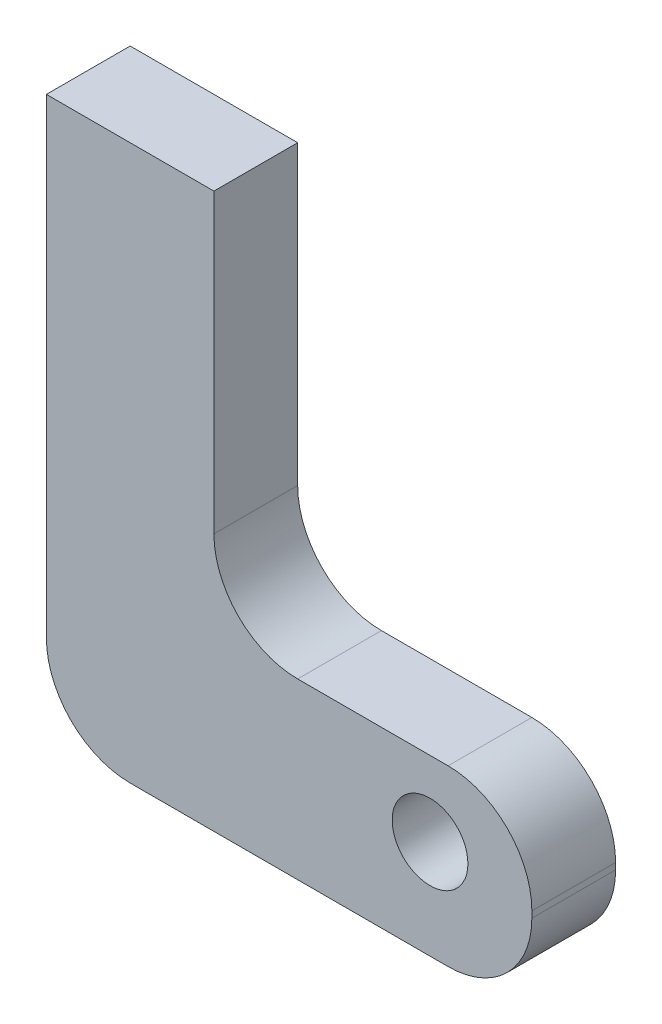
SolidWorks part; units mm, degrees
ref_plane "Front Plane" through (0, 0, 0) normal (0, 0, 1) x (1, 0, 0)
ref_plane "Top Plane" through (0, 0, 0) normal (0, 1, 0) x (1, 0, 0)
ref_plane "Right Plane" through (0, 0, 0) normal (1, 0, 0) x (0, 0, -1)
sketch "Sketch1" plane through (0, 0, 0) normal (0, 0, 1) x (1, 0, 0)
  line L1 (113.9499, 0) -> (126.6499, 0)
  line L2 (113.9499, 0) -> (113.9499, -6.35)
  line L4 (126.6499, 0) -> (126.6499, -6.35)
  line L6 (113.9499, -6.35) -> (113.9499, -42.0402)
  line L7 (113.9499, -42.0402) -> (126.6499, -42.0402)
  line L8 (126.6499, -6.35) -> (126.6499, -28.856)
  line L9 (126.6499, -42.0402) -> (150.7538, -42.0402)
  line L11 (126.6499, -28.856) -> (150.7538, -28.856)
  line L12 (150.7538, -42.0402) -> (150.7538, -28.856)
  circle A0 centre (143.0356, -34.5397) radius 2.8702
extrude "Boss-Extrude1" add sketch "Sketch1" along normal blind 6.35
fillet "Fillet1" radius 6.35 4 edges at (113.9499, -42.0402, 3.175) (150.7538, -42.0402, 3.175) (150.7538, -28.856, 3.175) (126.6499, -28.856, 3.175)
